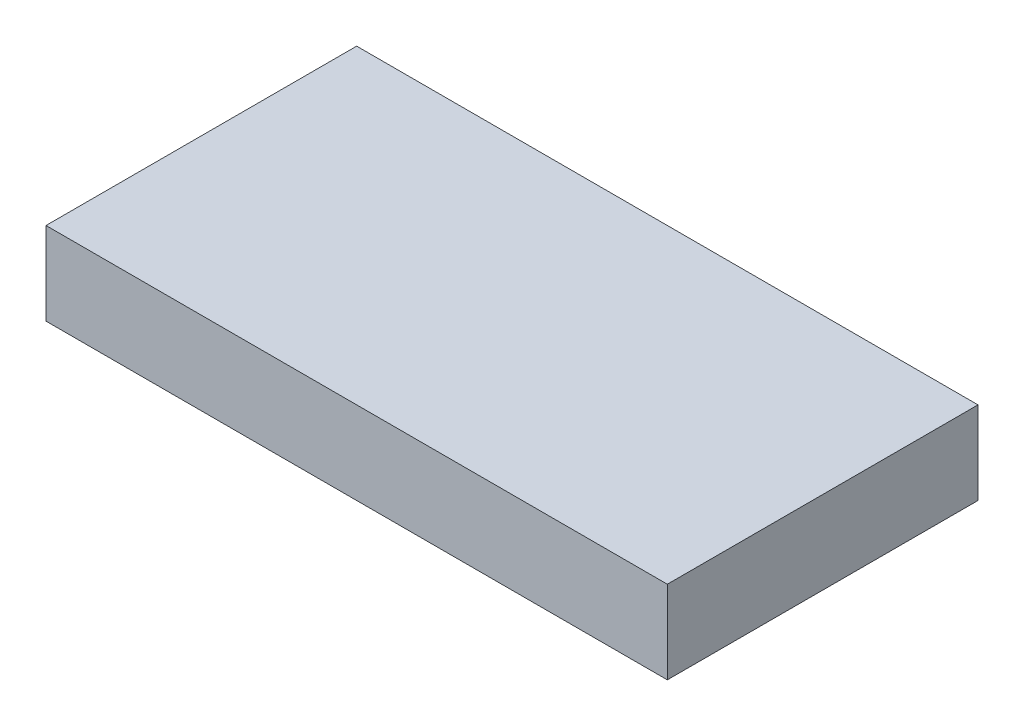
SolidWorks part; units mm, degrees
ref_plane "Plano frontal" through (0, 0, 0) normal (0, 0, 1) x (1, 0, 0)
ref_plane "Plano superior" through (0, 0, 0) normal (0, 1, 0) x (1, 0, 0)
ref_plane "Plano direito" through (0, 0, 0) normal (1, 0, 0) x (0, 0, -1)
sketch "Esboço1" plane through (0, 0, 0) normal (0, 1, 0) x (1, 0, 0)
  line L1 (-30, 15) -> (30, 15)
  line L2 (-30, 15) -> (-30, -15)
  line L3 (-30, -15) -> (30, -15)
  line L4 (30, 15) -> (30, -15)
  point P4 (0, 15)
  point P6 (30, 0)
  dimension "D1" = 60
  dimension "D2" = 30
extrude "Ressalto-extrusão1" add sketch "Esboço1" along normal blind 8
